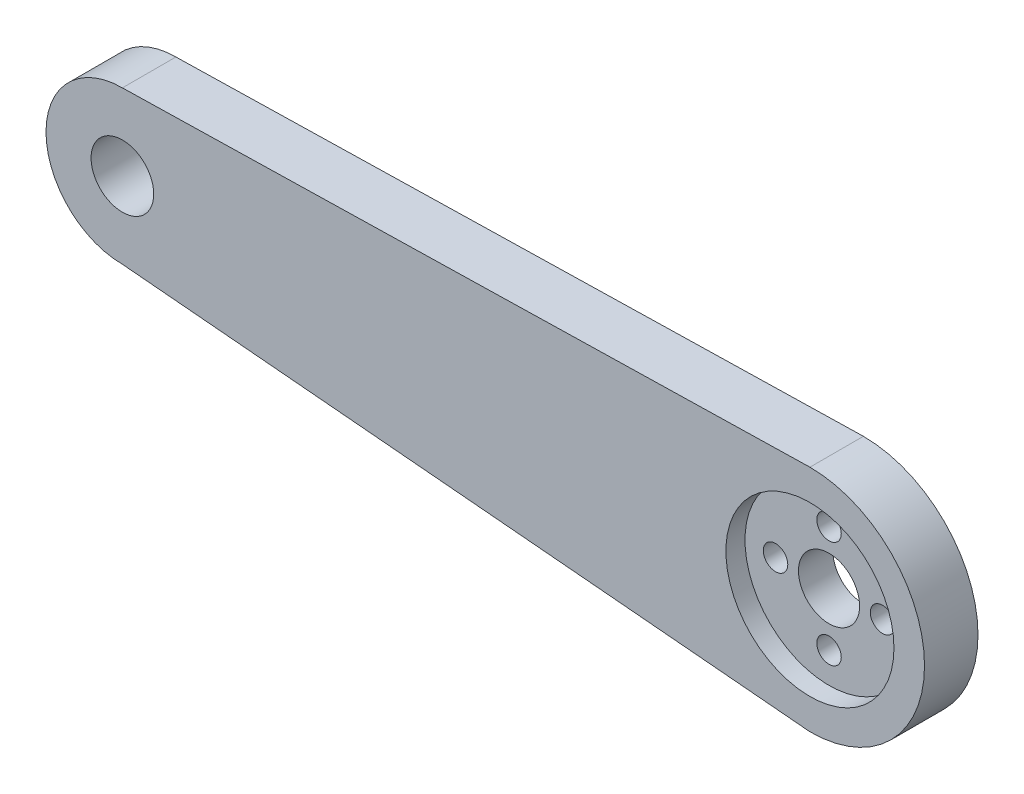
SolidWorks part; units mm, degrees
ref_plane "前视基准面" through (0, 0, 0) normal (0, 0, 1) x (1, 0, 0)
ref_plane "上视基准面" through (0, 0, 0) normal (0, 1, 0) x (1, 0, 0)
ref_plane "右视基准面" through (0, 0, 0) normal (1, 0, 0) x (0, 0, -1)
sketch "草图1" plane through (0, 0, 0) normal (0, 0, 1) x (1, 0, 0)
  line L0 (0, -10) -> (90, -18)
  line L3 (0, 10) -> (90, 12)
  arc A2 (90, -18) -> (90, 12) centre (90, -3) ccw
  arc A3 (0, 10) -> (0, -10) centre (0, 0) ccw
extrude "凸台-拉伸1" add sketch "草图1" along normal blind 7
sketch "草图2" plane through (0, 0, 0) normal (0, 0, -1) x (-1, 0, 0)
  circle A1 centre (0, 0) radius 4.1
  circle A2 centre (-90, -10) radius 1.6
  circle A3 centre (-83, -3) radius 1.6
  circle A4 centre (-90, 4) radius 1.6
  circle A5 centre (-97, -3) radius 1.6
  circle A6 centre (-90, -3) radius 4
  arc A8 (-90, 12) -> (-90, -18) centre (-90, -3) ccw construction
  point P17 (-90, -3)
  dimension "D1" = 4
  dimension "D2" = 7
extrude "切除-拉伸1" cut sketch "草图2" against normal blind 10
sketch "草图3" plane through (0, 0, 7) normal (0, 0, 1) x (1, 0, 0)
  circle A0 centre (90, -3) radius 11
extrude "切除-拉伸2" cut sketch "草图3" against normal blind 2.5
